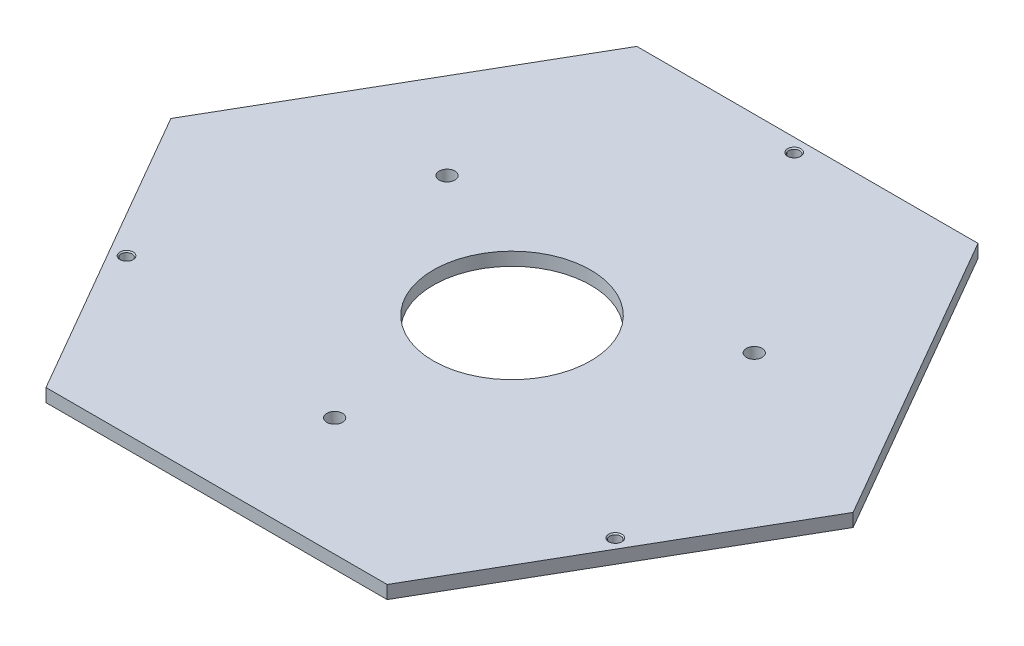
SolidWorks part; units mm, degrees
ref_plane "前视基准面" through (0, 0, 0) normal (0, 0, 1) x (1, 0, 0)
ref_plane "上视基准面" through (0, 0, 0) normal (0, 1, 0) x (1, 0, 0)
ref_plane "右视基准面" through (0, 0, 0) normal (1, 0, 0) x (0, 0, -1)
sketch "草图1" plane through (0, 0, 0) normal (0, 1, 0) x (1, 0, 0)
  line L1 (130, 0) -> (65, 112.5833)
  line L2 (65, 112.5833) -> (-65, 112.5833)
  line L3 (-65, 112.5833) -> (-130, 0)
  line L4 (-130, 0) -> (-65, -112.5833)
  line L5 (-65, -112.5833) -> (65, -112.5833)
  line L6 (65, -112.5833) -> (130, 0)
  circle A0 centre (0, 0) radius 112.5833 construction
  dimension "D1" = 130
extrude "凸台-拉伸1" add sketch "草图1" along normal blind 5
sketch "草图2" plane through (0, 5, 0) normal (0, 1, 0) x (1, 0, 0)
  circle A0 centre (0, 0) radius 30
extrude "切除-拉伸1" cut sketch "草图2" against normal blind 5
sketch "草图3" plane through (0, 5, 0) normal (0, 1, 0) x (1, 0, 0)
  line L0 (0, -112.5833) -> (0, 112.5833) construction
  line L1 (-65, -112.5833) -> (65, -112.5833) construction
  line L2 (65, 112.5833) -> (-65, 112.5833) construction
  line L3 (-97.5, 56.2917) -> (97.5, -56.2917) construction
  line L4 (-65, 112.5833) -> (-130, 0) construction
  line L5 (65, -112.5833) -> (130, 0) construction
  line L6 (97.5, 56.2917) -> (-97.5, -56.2917) construction
  line L7 (130, 0) -> (65, 112.5833) construction
  line L8 (-130, 0) -> (-65, -112.5833) construction
  circle A0 centre (-58.5289, 33.7917) radius 3
  circle A1 centre (58.5289, 33.7917) radius 3
  circle A2 centre (0, -67.5833) radius 3
  dimension "D1" = 45
  dimension "D2" = 45
  dimension "D3" = 45
extrude "切除-拉伸2" cut sketch "草图3" against normal blind 5
sketch "草图4" plane through (0, 5, 0) normal (0, 1, 0) x (1, 0, 0)
  line L0 (0, 112.5833) -> (0, 107.5333) construction
  line L1 (65, 112.5833) -> (-65, 112.5833) construction
  line L2 (-97.5, -56.2917) -> (-93.1266, -53.7667) construction
  line L3 (-130, 0) -> (-65, -112.5833) construction
  line L4 (97.5, -56.2917) -> (93.1266, -53.7667) construction
  line L5 (65, -112.5833) -> (130, 0) construction
  circle A0 centre (-93.1266, -53.7667) radius 2.5
  circle A1 centre (93.1266, -53.7667) radius 2.5
  circle A2 centre (0, 107.5333) radius 2.5
  point P1 (0, 107.5333)
  point P6 (-93.1266, -53.7667)
  point P10 (93.1266, -53.7667)
  point P25 (-93.1266, -53.7667)
  point P28 (-93.1266, -53.7667)
  point P30 (93.1266, -53.7667)
  point P32 (0, 107.5333)
  point P35 (0, 0)
  point P36 (0, 0)
hole_wizard "M5 螺纹孔3" positions "草图4" profile "草图6" tap size "M5" standard "GB" end condition through all
sketch "草图6" plane through (0, 5, -107.5333) normal (1, 0, 0) x (0, 0, 1)
  line L0 (0, 0) -> (0, 5)
  line L1 (0, 5) -> (2.1, 5)
  line L2 (2.1, 5) -> (2.1, 0.425)
  line L3 (2.1, 0.425) -> (2.525, 0)
  line L5 (2.525, 0) -> (0, 0)
  line L6 (-2.1, 0.425) -> (-2.525, 0) construction
  line L11 (0, -6.35) -> (0, 107.95) construction
  dimension "通孔螺纹孔钻头直径" = 4.2
  dimension "通孔螺纹孔钻头深度" = 5
  dimension "近端锥形沉头孔直径" = 5.05
  dimension "近端锥形沉头孔角度" = 90
cosmetic thread "孔螺蚊线2" parameters "D2"=5
cosmetic thread "孔螺蚊线3" parameters "D2"=5
cosmetic thread "孔螺蚊线5" parameters "D2"=5
